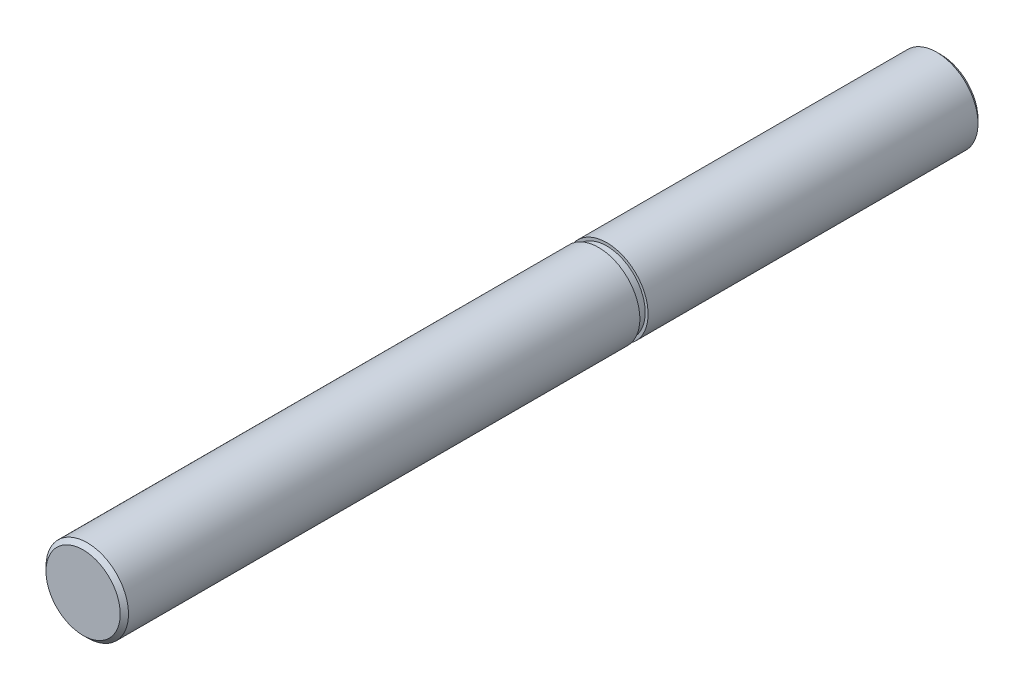
SolidWorks part; units mm, degrees
ref_plane "前视基准面" through (0, 0, 0) normal (0, 0, 1) x (1, 0, 0)
ref_plane "上视基准面" through (0, 0, 0) normal (0, 1, 0) x (1, 0, 0)
ref_plane "右视基准面" through (0, 0, 0) normal (1, 0, 0) x (0, 0, -1)
sketch "草图1" plane through (0, 0, 0) normal (0, 0, 1) x (1, 0, 0)
  circle A0 centre (0, 0) radius 5
  dimension "D1" = 10
extrude "拉伸1" add sketch "草图1" along normal blind 104
sketch "草图2" plane through (0, 0, 0) normal (0, 1, 0) x (1, 0, 0)
  line L0 (12.5, -41.5) -> (-12.5, -41.5) construction
  line L1 (4.65, -41.5) -> (8.1489, -41.5)
  line L2 (4.65, -41.5) -> (4.65, -40.5)
  line L3 (4.65, -40.5) -> (8.1489, -40.5)
  line L4 (8.1489, -41.5) -> (8.1489, -40.5)
  line L5 (5, -104) -> (5, 0) construction
  dimension "D1" = 1
  dimension "D2" = 0.35
revolve "切除-旋转1" cut sketch "草图2" angle 360 about axis through (0, 0, 104) along (0, 0, -1)
chamfer "倒角1" distance 0.5 angle 45 2 edges at (5, 0, 104) (5, 0, 0)
